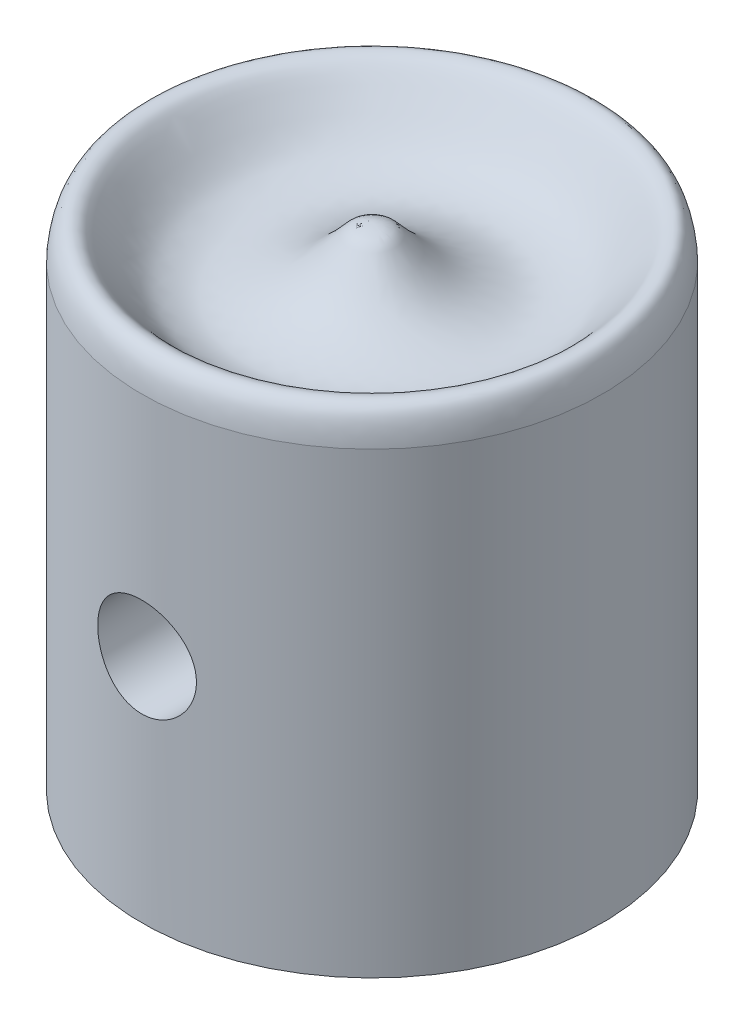
SolidWorks part; units mm, degrees
ref_plane "Ön Düzlem" through (0, 0, 0) normal (0, 0, 1) x (1, 0, 0)
ref_plane "Üst Düzlem" through (0, 0, 0) normal (0, 1, 0) x (1, 0, 0)
ref_plane "Sağ Düzlem" through (0, 0, 0) normal (1, 0, 0) x (0, 0, -1)
sketch "Sketch1" plane through (0, 0, 0) normal (0, 0, 1) x (1, 0, 0)
  line L0 (0, 2.4208) -> (0, -6.1354) construction
  line L4 (-7, 8.7121) -> (-7, 7.2957)
  line L5 (-7, -5.2043) -> (-6.25, -5.2043)
  line L6 (-6.25, -5.2043) -> (-5.0506, -1.9089)
  line L7 (-4.75, -0.2043) -> (-4.75, 4.4401)
  line L9 (0, 8.5662) -> (0, 9.6917)
  line L11 (0, 2.4208) -> (0, 8.5662) construction
  line L12 (-3.4761, 6.2594) -> (0, 7.5246)
  line L13 (0, 7.5246) -> (0, 8.5662)
  line L14 (-7, 5.7957) -> (-7, -5.2043)
  line L23 (-7, 6.7957) -> (-7, 6.2957)
  line L24 (-7, 7.2957) -> (-7, 6.7957)
  line L25 (-7, 6.2957) -> (-7, 5.7957)
  arc A0 (-3.4761, 6.2594) -> (-4.75, 4.4401) centre (-2.814, 4.4401) ccw
  arc A1 (-4.75, -0.2043) -> (-5.0506, -1.9089) centre (-9.7338, -0.2043) cw
  spline S0 degree 3 poles (-7, 8.7121) (-6.9159, 9.6729) (-6.5719, 9.7865) (-6.0171, 9.562) (-5.1735, 8.3204) (-3.9295, 7.778) (-3.2579, 7.7706) (-1.6216, 8.3745) (-0.9881, 9.0782) (-0.5143, 9.6341) (-0.1875, 9.6953) (0, 9.6917) knots 0 0 0 0 0.210747 0.254088 0.413487 0.459298 0.666392 0.71499 0.89668 0.927453 1 1 1 1
  point P5 (-2.375, 8.1)
  point P11 (-4.75, -0.2043)
  point P22 (-4.6517, 8.1)
  point P25 (-3.4761, 6.2594)
  point P26 (-4.75, 4.4401)
  point P30 (-5.0506, -1.9089)
  dimension "D10" = 4.6444
  dimension "D11" = 3.4761
  dimension "D1" = 7
  dimension "D2" = 0.5
  dimension "D5" = 6.25
  dimension "D6" = 5
  dimension "D7" = 20
  dimension "D8" = 3.2954
  dimension "D9" = 70
revolve "Revolve1" add sketch "Sketch1" angle 360 about L11
sketch "Sketch2" plane through (0, 0, 0) normal (0, 0, 1) x (1, 0, 0)
  line L0 (-7, -5.2043) -> (7, -5.2043) construction
  circle A0 centre (0, 1.7957) radius 1.5
  dimension "D1" = 7
extrude "Cut-Extrude1" cut sketch "Sketch2" against normal through all both and the other way through all
scale "Scale1" scale about centroid uniform scaling yes scale factor 1.5
